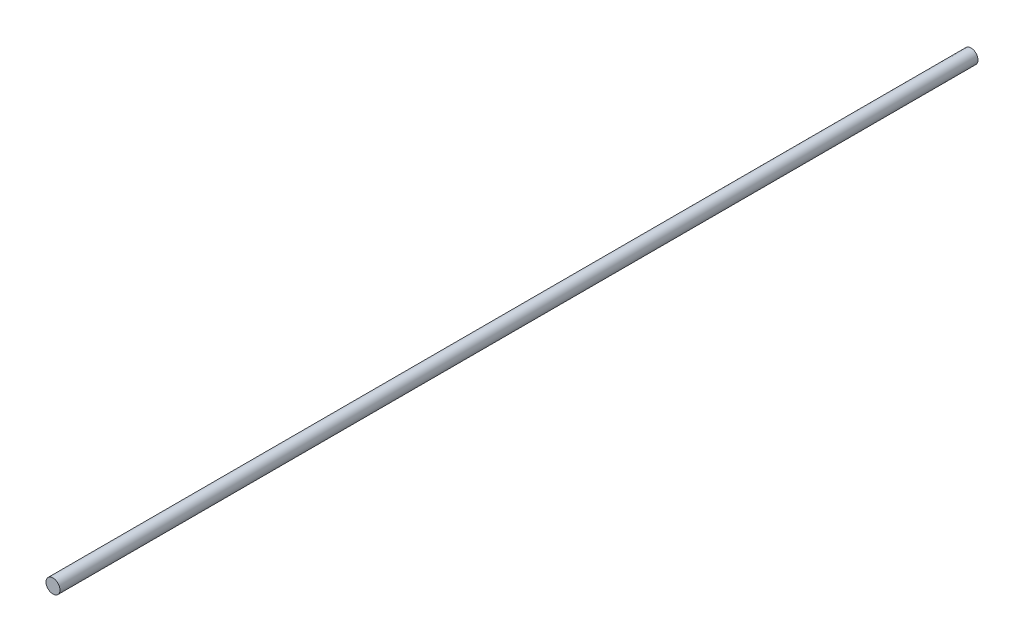
SolidWorks part; units mm, degrees
material "Hexcel AS4C (3000 Filaments)"
ref_plane "Front Plane" through (0, 0, 0) normal (0, 0, 1) x (1, 0, 0)
ref_plane "Top Plane" through (0, 0, 0) normal (0, 1, 0) x (1, 0, 0)
ref_plane "Right Plane" through (0, 0, 0) normal (1, 0, 0) x (0, 0, -1)
sketch "Sketch1" plane through (0, 0, 0) normal (0, 0, 1) x (1, 0, 0)
  circle A0 centre (0, 0) radius 1.5
  dimension "D1" = 3
extrude "Boss-Extrude1" add sketch "Sketch1" along normal mid plane 197
